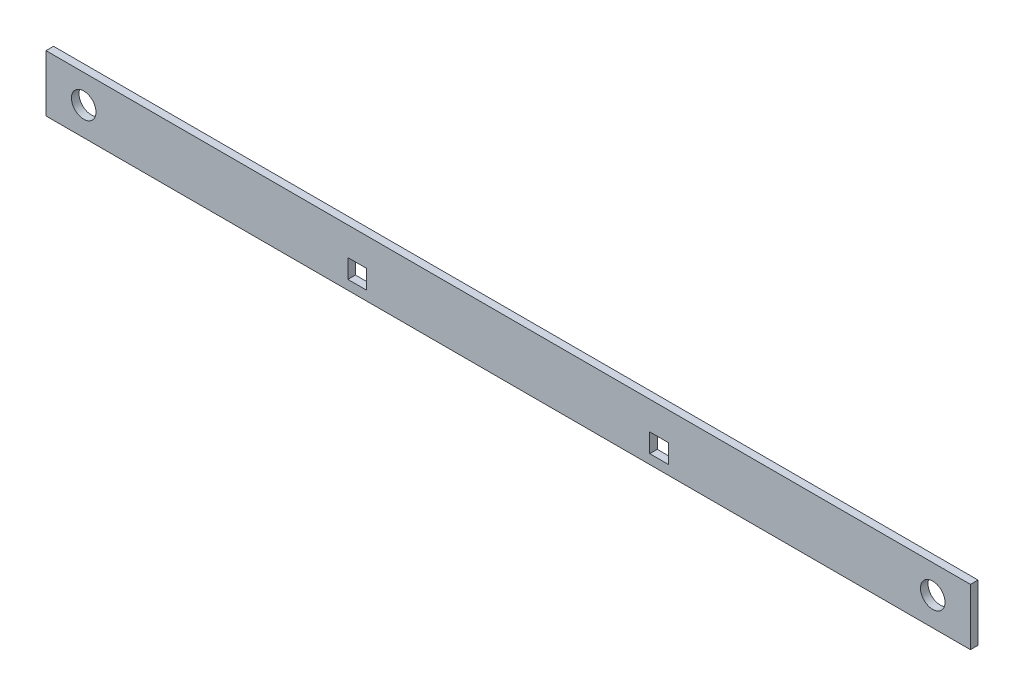
SolidWorks part; units mm, degrees
material "ABS"
ref_plane "Front Plane" through (0, 0, 0) normal (0, 0, 1) x (1, 0, 0)
ref_plane "Top Plane" through (0, 0, 0) normal (0, 1, 0) x (1, 0, 0)
ref_plane "Right Plane" through (0, 0, 0) normal (1, 0, 0) x (0, 0, -1)
sketch "Sketch1" plane through (0, 0, 0) normal (0, 0, 1) x (1, 0, 0)
  line L0 (-112.5, 0) -> (112.5, 0) construction
  line L2 (-122.5, -7.5) -> (122.5, -7.5)
  line L3 (-122.5, -7.5) -> (-122.5, 7.5)
  line L4 (-122.5, 7.5) -> (122.5, 7.5)
  line L5 (122.5, -7.5) -> (122.5, 7.5)
  line L6 (-122.5, -7.5) -> (122.5, 7.5) construction
  line L7 (-122.5, 7.5) -> (122.5, -7.5) construction
  circle A0 centre (-112.5, 0) radius 3.25
  circle A1 centre (112.5, 0) radius 3.25
  point P4 (0, 0)
  point P5 (0, 0)
  dimension "D1" = 6.5
  dimension "D2" = 15
  dimension "D3" = 225
  dimension "D4" = 10
extrude "Boss-Extrude1" add sketch "Sketch1" along normal blind 2
sketch "Sketch2" plane through (0, 0, 2) normal (0, 0, 1) x (1, 0, 0)
  line L0 (-40, -2.5) -> (40, -2.5) construction
  line L1 (-42.5, -5) -> (-37.5, -5)
  line L2 (-42.5, -5) -> (-42.5, 0)
  line L3 (-42.5, 0) -> (-37.5, 0)
  line L4 (-37.5, -5) -> (-37.5, 0)
  line L5 (-42.5, -5) -> (-37.5, 0) construction
  line L6 (-42.5, 0) -> (-37.5, -5) construction
  line L7 (37.5, -5) -> (42.5, -5)
  line L8 (37.5, -5) -> (37.5, 0)
  line L9 (37.5, 0) -> (42.5, 0)
  line L10 (42.5, -5) -> (42.5, 0)
  line L11 (37.5, -5) -> (42.5, 0) construction
  line L12 (37.5, 0) -> (42.5, -5) construction
  point P0 (-40, -2.5)
  point P5 (40, -2.5)
  point P12 (0, -2.5)
  dimension "D1" = 80
  dimension "D2" = 5
  dimension "D3" = 2.5
extrude "Cut-Extrude1" cut sketch "Sketch2" against normal blind 10
